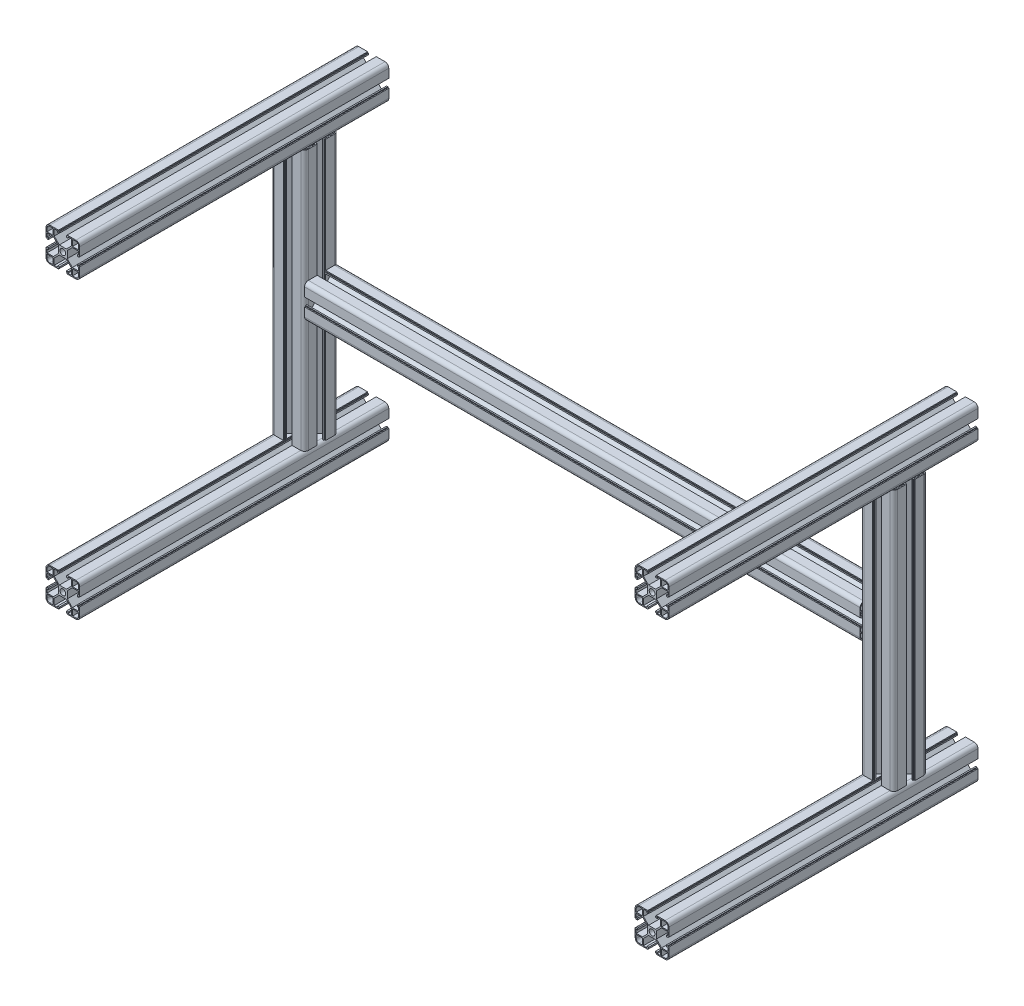
SolidWorks part; units mm, degrees
material "6063-T5"
ref_plane "前视基准面" through (0, 0, 0) normal (0, 0, 1) x (1, 0, 0)
ref_plane "上视基准面" through (0, 0, 0) normal (0, 1, 0) x (1, 0, 0)
ref_plane "右视基准面" through (0, 0, 0) normal (1, 0, 0) x (0, 0, -1)
sketch3d "3D草图2"
  line L0 (-350, 175, 0) -> (-350, 175, 367.21)
  line L1 (-350, -175, 0) -> (350, -175, 0) construction
  line L2 (-350, -175, 0) -> (-350, 175, 0) construction
  line L3 (-350, 175, 0) -> (350, 175, 0) construction
  line L4 (350, -175, 0) -> (350, 175, 0) construction
  line L5 (-350, -175, 0) -> (350, 175, 0) construction
  line L6 (-350, 175, 0) -> (350, -175, 0) construction
  line L7 (-350, -175, 0) -> (-350, -175, 367.21)
  line L8 (350, -175, 0) -> (350, -175, 367.21)
  line L9 (350, 175, 0) -> (350, 175, 367.21)
  line L10 (-350, 0, 80) -> (350, 0, 80)
  line L11 (-350, -175, 80) -> (350, -175, 80) construction
  line L12 (-350, -175, 80) -> (-350, 175, 80)
  line L13 (-350, 175, 80) -> (350, 175, 80) construction
  line L14 (350, -175, 80) -> (350, 175, 80)
  point P0 (0, 0, 0)
  point P16 (350, 0, 80)
  dimension "D1" = 350
  dimension "D2" = 700
  dimension "D3" = 80
  dimension "D4" = 367.21
other "欧标4040-厚1.5 欧标4040厚1.5(1)"
ref_plane "基准面5" through (-350, -175, 0) normal (0, 0, 1) x (1, 0, 0)
sketch "草图1" plane through (-350, -175, 0) normal (0, 0, 1) x (1, 0, 0)
  line L0 (0, 20) -> (0, -20) construction
  line L1 (0, 0) -> (-20, 0) construction
  line L2 (-5.25, -4.1893) -> (-5.25, 4.1893)
  line L3 (-5.25, 4.1893) -> (-11.3107, 10.25)
  line L4 (-11.3107, 10.25) -> (-18.8, 10.25)
  line L5 (-18.8, 10.25) -> (-18.8, 6.1)
  line L6 (-18.8, 6.1) -> (-17.3, 6.1)
  line L7 (-17.3, 6.1) -> (-17.3, 4.1)
  line L8 (-17.3, 4.1) -> (-18.8, 4.1)
  line L9 (-18.8, 4.1) -> (-18.8, 5.1)
  line L10 (-18.8, 5.1) -> (-20, 5.1)
  line L11 (-20, 5.1) -> (-20, 15.5)
  line L12 (-20, 20) -> (0, 0) construction
  line L13 (-11.45, 11.45) -> (-18.8, 11.45)
  line L14 (-18.8, 11.45) -> (-18.8, 15.5)
  line L15 (-4.1893, 5.25) -> (-10.25, 11.3107)
  line L16 (4.1893, 5.25) -> (-4.1893, 5.25)
  line L17 (-11.45, 18.8) -> (-15.5, 18.8)
  line L18 (-11.45, 11.45) -> (-11.45, 18.8)
  line L19 (-5.1, 20) -> (-15.5, 20)
  line L20 (-5.1, 18.8) -> (-5.1, 20)
  line L21 (-4.1, 18.8) -> (-5.1, 18.8)
  line L22 (-4.1, 17.3) -> (-4.1, 18.8)
  line L23 (-6.1, 17.3) -> (-4.1, 17.3)
  line L24 (-6.1, 18.8) -> (-6.1, 17.3)
  line L25 (-10.25, 18.8) -> (-6.1, 18.8)
  line L26 (-10.25, 11.3107) -> (-10.25, 18.8)
  line L27 (4.1893, 5.25) -> (10.25, 11.3107)
  line L28 (5.25, 4.1893) -> (11.3107, 10.25)
  line L29 (5.25, -4.1893) -> (5.25, 4.1893)
  line L30 (11.45, 11.45) -> (18.8, 11.45)
  line L31 (18.8, 5.1) -> (20, 5.1)
  line L32 (18.8, 4.1) -> (18.8, 5.1)
  line L33 (17.3, 4.1) -> (18.8, 4.1)
  line L34 (17.3, 6.1) -> (17.3, 4.1)
  line L35 (18.8, 6.1) -> (17.3, 6.1)
  line L36 (18.8, 10.25) -> (18.8, 6.1)
  line L37 (11.3107, 10.25) -> (18.8, 10.25)
  line L38 (18.8, 11.45) -> (18.8, 15.5)
  line L39 (20, 5.1) -> (20, 15.5)
  line L40 (10.25, 11.3107) -> (10.25, 18.8)
  line L41 (10.25, 18.8) -> (6.1, 18.8)
  line L42 (6.1, 18.8) -> (6.1, 17.3)
  line L43 (6.1, 17.3) -> (4.1, 17.3)
  line L44 (4.1, 17.3) -> (4.1, 18.8)
  line L45 (4.1, 18.8) -> (5.1, 18.8)
  line L46 (5.1, 18.8) -> (5.1, 20)
  line L47 (5.1, 20) -> (15.5, 20)
  line L48 (11.45, 11.45) -> (11.45, 18.8)
  line L49 (11.45, 18.8) -> (15.5, 18.8)
  line L50 (20, 20) -> (0, 0) construction
  line L51 (-17.3, -4.1) -> (-18.8, -4.1)
  line L52 (20, -20) -> (0, 0) construction
  line L53 (-20, -20) -> (0, 0) construction
  line L54 (11.45, -18.8) -> (15.5, -18.8)
  line L55 (11.45, -11.45) -> (11.45, -18.8)
  line L56 (5.1, -20) -> (15.5, -20)
  line L57 (5.1, -18.8) -> (5.1, -20)
  line L58 (4.1, -18.8) -> (5.1, -18.8)
  line L59 (4.1, -17.3) -> (4.1, -18.8)
  line L60 (6.1, -17.3) -> (4.1, -17.3)
  line L61 (6.1, -18.8) -> (6.1, -17.3)
  line L62 (10.25, -18.8) -> (6.1, -18.8)
  line L63 (10.25, -11.3107) -> (10.25, -18.8)
  line L64 (20, -5.1) -> (20, -15.5)
  line L65 (18.8, -11.45) -> (18.8, -15.5)
  line L66 (11.3107, -10.25) -> (18.8, -10.25)
  line L67 (18.8, -10.25) -> (18.8, -6.1)
  line L68 (18.8, -6.1) -> (17.3, -6.1)
  line L69 (17.3, -6.1) -> (17.3, -4.1)
  line L70 (18.8, -4.1) -> (18.8, -5.1)
  line L71 (18.8, -5.1) -> (20, -5.1)
  line L72 (11.45, -11.45) -> (18.8, -11.45)
  line L73 (5.25, -4.1893) -> (11.3107, -10.25)
  line L74 (4.1893, -5.25) -> (10.25, -11.3107)
  line L75 (-10.25, -11.3107) -> (-10.25, -18.8)
  line L76 (-10.25, -18.8) -> (-6.1, -18.8)
  line L77 (-6.1, -18.8) -> (-6.1, -17.3)
  line L78 (-6.1, -17.3) -> (-4.1, -17.3)
  line L79 (-4.1, -17.3) -> (-4.1, -18.8)
  line L80 (-4.1, -18.8) -> (-5.1, -18.8)
  line L81 (-5.1, -18.8) -> (-5.1, -20)
  line L82 (-5.1, -20) -> (-15.5, -20)
  line L83 (-11.45, -11.45) -> (-11.45, -18.8)
  line L84 (-11.45, -18.8) -> (-15.5, -18.8)
  line L85 (4.1893, -5.25) -> (-4.1893, -5.25)
  line L86 (-4.1893, -5.25) -> (-10.25, -11.3107)
  line L87 (-18.8, -11.45) -> (-18.8, -15.5)
  line L88 (-11.45, -11.45) -> (-18.8, -11.45)
  line L89 (-20, -5.1) -> (-20, -15.5)
  line L90 (-18.8, -5.1) -> (-20, -5.1)
  line L91 (-18.8, -4.1) -> (-18.8, -5.1)
  line L92 (-17.3, -6.1) -> (-17.3, -4.1)
  line L93 (-18.8, -6.1) -> (-17.3, -6.1)
  line L94 (-18.8, -10.25) -> (-18.8, -6.1)
  line L95 (-11.3107, -10.25) -> (-18.8, -10.25)
  line L96 (-5.25, -4.1893) -> (-11.3107, -10.25)
  line L97 (17.3, -4.1) -> (18.8, -4.1)
  circle A0 centre (0, 0) radius 3.4
  arc A1 (-20, 15.5) -> (-15.5, 20) centre (-15.5, 15.5) cw
  arc A2 (-18.8, 15.5) -> (-15.5, 18.8) centre (-15.5, 15.5) cw
  arc A3 (18.8, 15.5) -> (15.5, 18.8) centre (15.5, 15.5) ccw
  arc A4 (20, 15.5) -> (15.5, 20) centre (15.5, 15.5) ccw
  arc A5 (20, -15.5) -> (15.5, -20) centre (15.5, -15.5) cw
  arc A6 (18.8, -15.5) -> (15.5, -18.8) centre (15.5, -15.5) cw
  arc A7 (-18.8, -15.5) -> (-15.5, -18.8) centre (-15.5, -15.5) ccw
  arc A8 (-20, -15.5) -> (-15.5, -20) centre (-15.5, -15.5) ccw
  point P35 (-18.8, 18.8)
  point P38 (0, 5.25)
  point P65 (-5.25, 0)
  point P66 (5.25, 0)
  point P119 (0, -5.25)
  point P120 (-18.8, -18.8)
  point P121 (0, 0)
  dimension "D3" = 6.8
  dimension "D14" = 4.5
  dimension "D15" = 3.3
  dimension "D1" = 40
  dimension "D4" = 10.5
  dimension "D5" = 1.5
  dimension "D6" = 8.2
  dimension "D7" = 10.2
  dimension "D8" = 1.2
  dimension "D10" = 1.5
  dimension "D11" = 1.2
  dimension "D12" = 1
  dimension "D13" = 20.5
